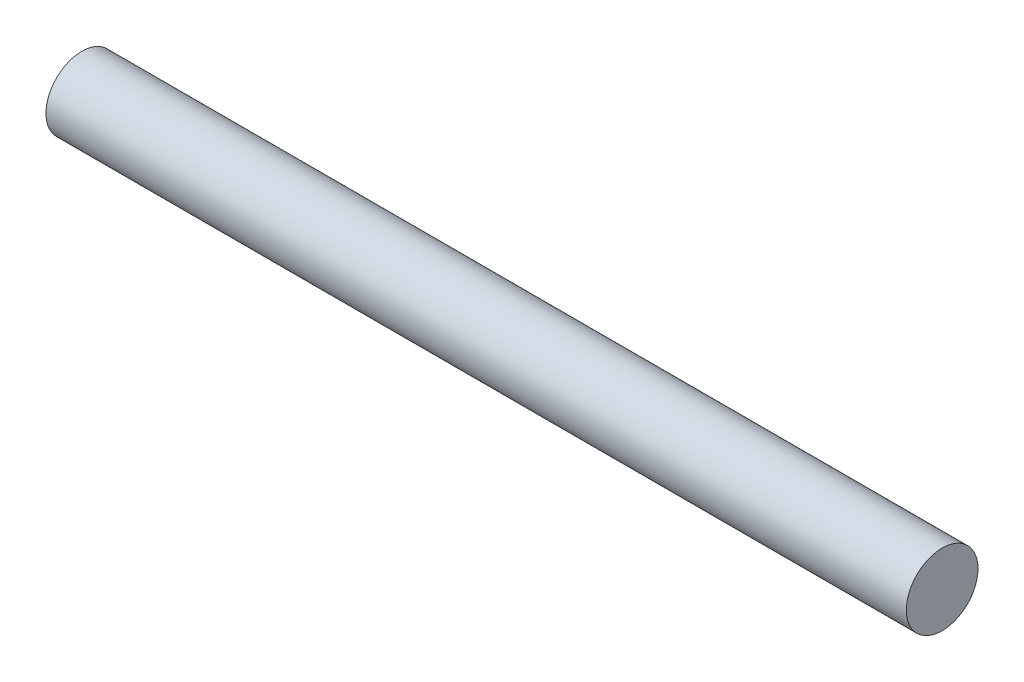
SolidWorks part; units mm, degrees
ref_plane "Plano frontal" through (0, 0, 0) normal (0, 0, 1) x (1, 0, 0)
ref_plane "Plano superior" through (0, 0, 0) normal (0, 1, 0) x (1, 0, 0)
ref_plane "Plano direito" through (0, 0, 0) normal (1, 0, 0) x (0, 0, -1)
sketch3d "SUSP_rack_housing_eixo"
  line L0 (-240, -90.4, -82.3915) -> (240, -90.4, -82.3915)
sweep "SUSP_rack_housing" add path "SUSP_rack_housing_eixo" circular profile diameter 40 parameters "D3"=40
